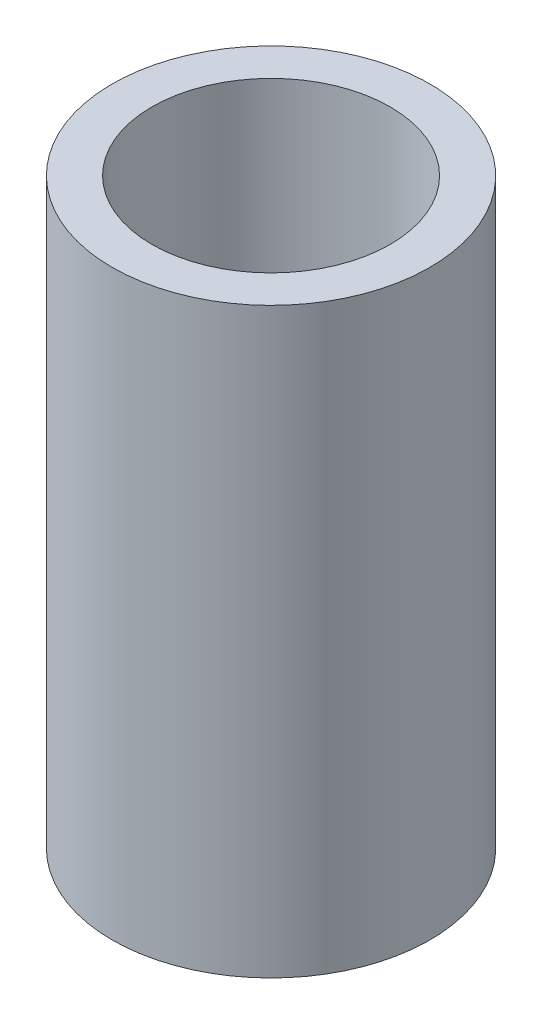
SolidWorks part; units mm, degrees
ref_plane "Plan de face" through (0, 0, 0) normal (0, 0, 1) x (1, 0, 0)
ref_plane "Plan de dessus" through (0, 0, 0) normal (0, 1, 0) x (1, 0, 0)
ref_plane "Plan de droite" through (0, 0, 0) normal (1, 0, 0) x (0, 0, -1)
sketch "Esquisse1" plane through (0, 0, 0) normal (0, 1, 0) x (1, 0, 0)
  circle A0 centre (0, 0) radius 2.25
  circle A1 centre (0, 0) radius 3
  dimension "D1" = 4.5
  dimension "D2" = 6
extrude "Boss.-Extru.1" add sketch "Esquisse1" along normal blind 11
